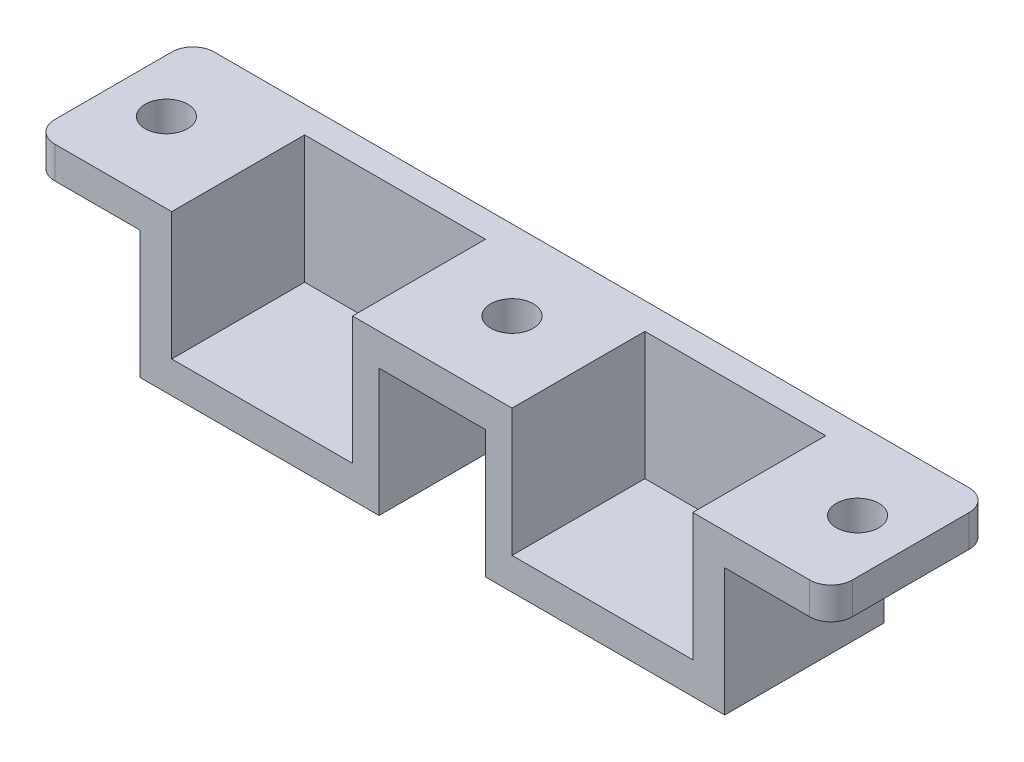
SolidWorks part; units mm, degrees
ref_plane "Front" through (0, 0, 0) normal (0, 0, 1) x (1, 0, 0)
ref_plane "Top" through (0, 0, 0) normal (0, 1, 0) x (1, 0, 0)
ref_plane "Right" through (0, 0, 0) normal (1, 0, 0) x (0, 0, -1)
sketch "Sketch1" plane through (0, 0, 0) normal (0, 1, 0) x (1, 0, 0)
  line L1 (37.5, -7.5) -> (-37.5, -7.5)
  line L2 (37.5, -7.5) -> (37.5, 7.5)
  line L3 (37.5, 7.5) -> (-37.5, 7.5)
  line L4 (-37.5, -7.5) -> (-37.5, 7.5)
  line L5 (37.5, -7.5) -> (-37.5, 7.5) construction
  line L6 (37.5, 7.5) -> (-37.5, -7.5) construction
  point P0 (0, 0)
  dimension "D1" = 75
  dimension "D2" = 15
extrude "Boss-Extrude1" add sketch "Sketch1" along normal blind 15
sketch "Sketch2" plane through (0, 15, 0) normal (0, 1, 0) x (1, 0, 0)
  line L0 (-37.5, -7.5) -> (37.5, -7.5) construction
  line L1 (-24.5, -7.5) -> (-7.5, -7.5)
  line L2 (-24.5, -7.5) -> (-24.5, 5)
  line L3 (-24.5, 5) -> (-7.5, 5)
  line L4 (-7.5, -7.5) -> (-7.5, 5)
  line L5 (37.5, 7.5) -> (-37.5, 7.5) construction
  line L6 (7.5, -7.5) -> (24.5, -7.5)
  line L7 (7.5, -7.5) -> (7.5, 5)
  line L8 (7.5, 5) -> (24.5, 5)
  line L9 (24.5, -7.5) -> (24.5, 5)
  line L10 (-37.5, 7.5) -> (-37.5, -7.5) construction
  dimension "D1" = 17
  dimension "D2" = 2.5
  dimension "D3" = 15
  dimension "D4" = 13
extrude "Cut-Extrude1" cut sketch "Sketch2" against normal blind 12
sketch "Sketch3" plane through (0, 0, 0) normal (0, -1, 0) x (1, 0, 0)
  line L0 (-37.5, 7.5) -> (37.5, 7.5) construction
  line L1 (-37.5, -7.5) -> (-27.5, -7.5)
  line L2 (-37.5, -7.5) -> (-37.5, 7.5)
  line L3 (-37.5, 7.5) -> (-27.5, 7.5)
  line L4 (-27.5, -7.5) -> (-27.5, 7.5)
  line L6 (37.5, -7.5) -> (27.5, -7.5)
  line L7 (37.5, -7.5) -> (37.5, 7.5)
  line L8 (37.5, 7.5) -> (27.5, 7.5)
  line L9 (27.5, -7.5) -> (27.5, 7.5)
  line L10 (5, -7.5) -> (-5, -7.5)
  line L11 (5, -7.5) -> (5, 7.5)
  line L12 (5, 7.5) -> (-5, 7.5)
  line L13 (-5, -7.5) -> (-5, 7.5)
  line L14 (5, -7.5) -> (-5, 7.5) construction
  line L15 (5, 7.5) -> (-5, -7.5) construction
  point P12 (0, 0)
  dimension "D1" = 10
  dimension "D2" = 10
extrude "Cut-Extrude2" cut sketch "Sketch3" against normal blind 12
hole_wizard "Ø4.0mm Dowel Hole2" positions "Sketch4" profile "Sketch5" hole size "Ø4.0" standard "ANSI Metric" end condition through all
sketch "Sketch4" plane through (0, 12, 0) normal (0, -1, 0) x (-1, 0, 0)
  line L0 (-37.5, 7.5) -> (-37.5, -7.5) construction
  line L1 (37.5, -7.5) -> (37.5, 7.5) construction
  point P0 (32.5, 0)
  point P2 (0, 0)
  point P5 (-32.5, 0)
  point P15 (0, 0)
  dimension "D1" = 5
  dimension "D2" = 5
sketch "Sketch5" plane through (-32.5, 12, 0) normal (1, 0, 0) x (0, 0, -1)
  line L0 (0, 0) -> (0, 3)
  line L1 (0, 3) -> (2, 3)
  line L2 (2, 3) -> (2, 0)
  line L5 (2, 0) -> (0, 0)
  line L11 (0, -6.35) -> (0, 107.95) construction
  dimension "Thru Hole Dia." = 4
  dimension "Thru Hole Depth" = 3
fillet "Fillet1" radius 2 4 edges at (-37.5, 13.5, -7.5) (-37.5, 13.5, 7.5) (37.5, 13.5, 7.5) (37.5, 13.5, -7.5)
